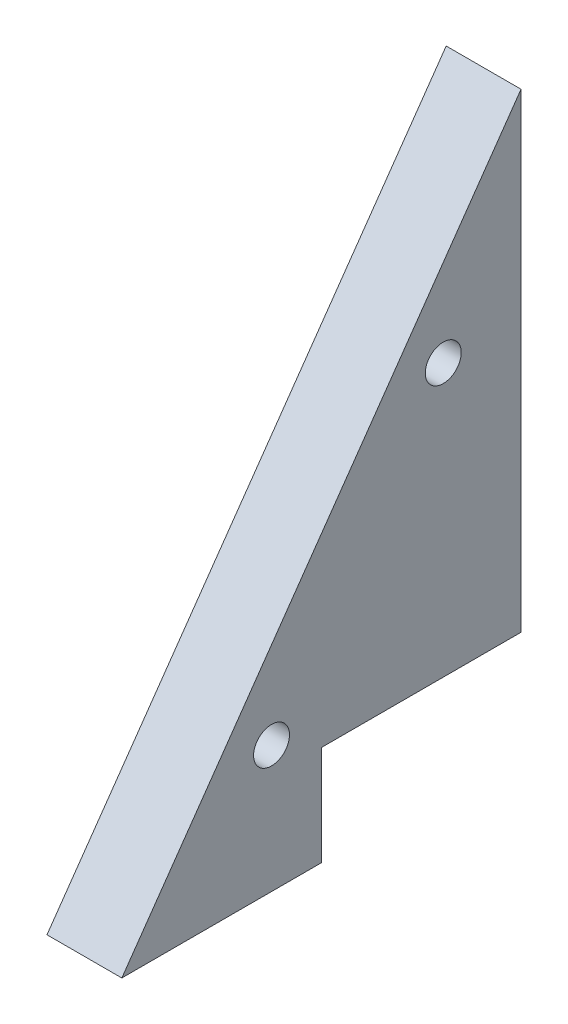
SolidWorks part; units mm, degrees
ref_plane "Front Plane" through (0, 0, 0) normal (0, 0, 1) x (1, 0, 0)
ref_plane "Top Plane" through (0, 0, 0) normal (0, 1, 0) x (1, 0, 0)
ref_plane "Right Plane" through (0, 0, 0) normal (1, 0, 0) x (0, 0, -1)
sketch "Sketch1" plane through (0, 0, 0) normal (1, 0, 0) x (0, 0, -1)
  line L0 (0, 0) -> (-25.4, 0)
  line L1 (-25.4, 0) -> (25.4, 72.5499)
  line L2 (25.4, 72.5499) -> (25.4, 12.7)
  line L3 (25.4, 12.7) -> (0, 12.7)
  line L4 (0, 12.7) -> (0, 0)
  dimension "D1" = 12.7
  dimension "D2" = 25.4
  dimension "D3" = 55
  dimension "D4" = 25.4
extrude "Boss-Extrude1" add sketch "Sketch1" along normal blind 9.525
sketch "Sketch2" plane through (0, 12.7, 0) normal (0, -1, 0) x (1, 0, 0)
  line L0 (0, 0) -> (0, -25.4) construction
  line L1 (9.525, -25.4) -> (0, -25.4) construction
  circle A1 centre (4.7625, -19.05) radius 1.905
  circle A2 centre (4.7625, -6.35) radius 1.905
  dimension "D2" = 3.81
  dimension "D3" = 6.35
  dimension "D1" = 4.7625
  dimension "D4" = 2
extrude "Cut-Extrude1" cut sketch "Sketch2" against normal blind 9.525
sketch "Sketch3" plane through (9.525, 0, 0) normal (1, 0, 0) x (0, 0, -1)
  line L0 (15.5033, 47.345) -> (-6.35, 16.1353) construction
  line L2 (25.4, 72.5499) -> (-25.4, 0) construction
  line L3 (0, 0) -> (0, 12.7) construction
  circle A0 centre (-6.35, 16.1353) radius 2.286
  circle A1 centre (15.5033, 47.345) radius 2.286
  dimension "D3" = 4.572
  dimension "D4" = 6.35
  dimension "D1" = 38.1
  dimension "D2" = 6.35
extrude "Cut-Extrude2" cut sketch "Sketch3" against normal through all
